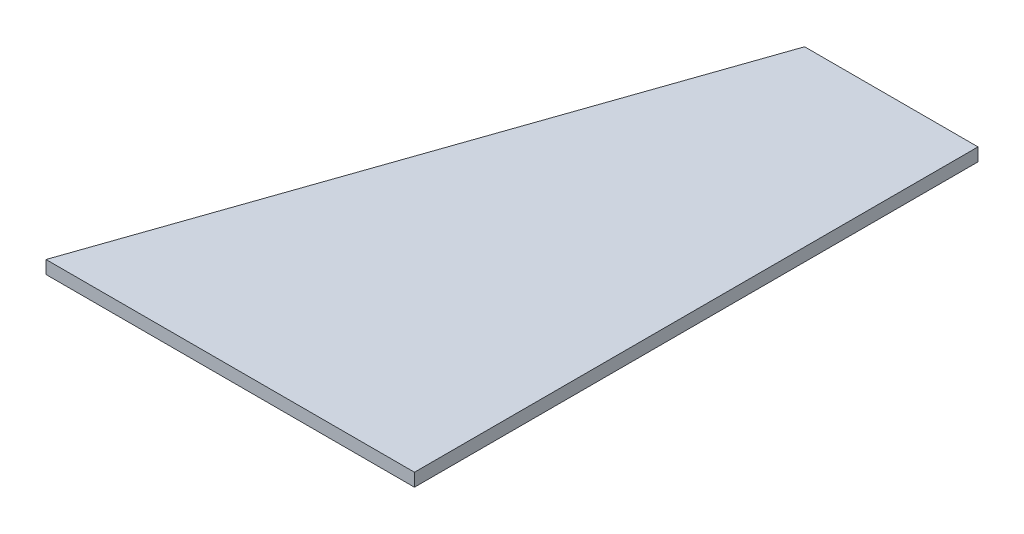
SolidWorks part; units mm, degrees
ref_plane "Front Plane" through (0, 0, 0) normal (0, 0, 1) x (1, 0, 0)
ref_plane "Top Plane" through (0, 0, 0) normal (0, 1, 0) x (1, 0, 0)
ref_plane "Right Plane" through (0, 0, 0) normal (1, 0, 0) x (0, 0, -1)
sketch "Sketch1" plane through (0, 0, 0) normal (0, 1, 0) x (1, 0, 0)
  line L0 (170, 260) -> (90, 260)
  line L1 (0, 0) -> (170, 0)
  line L4 (170, 0) -> (170, 260)
  line L5 (90, 260) -> (0, 0)
  dimension "D1" = 170
  dimension "D2" = 260
  dimension "D3" = 80
extrude "Boss-Extrude1" add sketch "Sketch1" along normal mid plane 6
